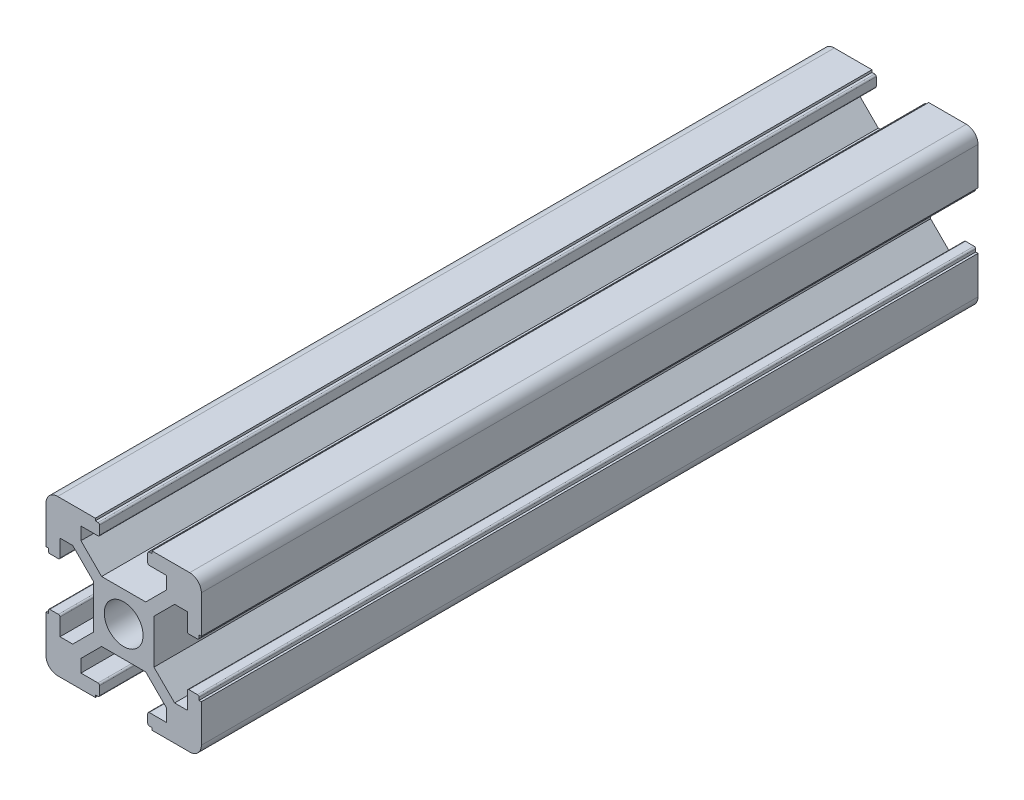
SolidWorks part; units mm, degrees
ref_plane "前视基准面" through (0, 0, 0) normal (0, 0, 1) x (1, 0, 0)
ref_plane "上视基准面" through (0, 0, 0) normal (0, 1, 0) x (1, 0, 0)
ref_plane "右视基准面" through (0, 0, 0) normal (1, 0, 0) x (0, 0, -1)
sketch "草图1" plane through (0, 0, 0) normal (0, 0, 1) x (1, 0, 0)
  line L0 (-17.5, 0) -> (33.5, 0) construction
  line L1 (0, 35.5833) -> (0, -31.0833) construction
  line L2 (3.65, 10) -> (8.5, 10)
  line L3 (10, 10) -> (10, -10) construction
  line L4 (-2.8393, 3.9) -> (2.8393, 3.9)
  line L5 (3.9, 2.8393) -> (3.9, -2.8393)
  line L6 (5.5, 8.2) -> (5.5, 6.5607)
  line L7 (3.9, 3.9) -> (10, 10) construction
  line L8 (4.4303, 3.3697) -> (6.5607, 5.5) construction
  line L9 (3.65, 10) -> (3.65, 8.2)
  line L10 (3.65, 8.2) -> (5.5, 8.2)
  line L11 (3.3697, 4.4303) -> (5.5, 6.5607) construction
  line L12 (5.5, 6.5607) -> (2.8393, 3.9)
  line L13 (6.5607, 5.5) -> (3.9, 2.8393)
  line L14 (3.3697, 4.4303) -> (9.4697, 10.5303) construction
  line L15 (4.4303, 3.3697) -> (10.5303, 9.4697) construction
  line L16 (8.2, 5.5) -> (6.5607, 5.5)
  line L17 (8.2, 3.65) -> (8.2, 5.5)
  line L18 (10, 3.65) -> (10, 8.5)
  line L19 (10, 3.65) -> (8.2, 3.65)
  line L20 (-3.3697, 4.4303) -> (-5.5, 6.5607) construction
  line L21 (-4.4303, 3.3697) -> (-6.5607, 5.5) construction
  line L22 (-3.9, 3.9) -> (-10, 10) construction
  line L23 (-10, 10) -> (-10, -10) construction
  line L24 (-10, 3.65) -> (-8.2, 3.65)
  line L25 (-10, 3.65) -> (-10, 8.5)
  line L26 (-8.2, 3.65) -> (-8.2, 5.5)
  line L27 (-8.2, 5.5) -> (-6.5607, 5.5)
  line L28 (-6.5607, 5.5) -> (-3.9, 2.8393)
  line L29 (-5.5, 6.5607) -> (-2.8393, 3.9)
  line L30 (-3.65, 8.2) -> (-5.5, 8.2)
  line L31 (-3.65, 10) -> (-3.65, 8.2)
  line L32 (-5.5, 8.2) -> (-5.5, 6.5607)
  line L33 (-3.9, 2.8393) -> (-3.9, -2.8393)
  line L34 (-3.65, 10) -> (-8.5, 10)
  line L35 (-3.9, -3.9) -> (-10, -10) construction
  line L36 (-4.4303, -3.3697) -> (-6.5607, -5.5) construction
  line L37 (-3.3697, -4.4303) -> (-5.5, -6.5607) construction
  line L38 (3.3697, -4.4303) -> (5.5, -6.5607) construction
  line L39 (4.4303, -3.3697) -> (6.5607, -5.5) construction
  line L40 (3.9, -3.9) -> (10, -10) construction
  line L41 (-3.65, -10) -> (-8.5, -10)
  line L42 (-5.5, -8.2) -> (-5.5, -6.5607)
  line L43 (-3.65, -10) -> (-3.65, -8.2)
  line L44 (-3.65, -8.2) -> (-5.5, -8.2)
  line L45 (-5.5, -6.5607) -> (-2.8393, -3.9)
  line L46 (-6.5607, -5.5) -> (-3.9, -2.8393)
  line L47 (-8.2, -5.5) -> (-6.5607, -5.5)
  line L48 (-8.2, -3.65) -> (-8.2, -5.5)
  line L49 (-10, -3.65) -> (-10, -8.5)
  line L50 (-10, -3.65) -> (-8.2, -3.65)
  line L51 (10, -3.65) -> (8.2, -3.65)
  line L52 (10, -3.65) -> (10, -8.5)
  line L53 (8.2, -3.65) -> (8.2, -5.5)
  line L54 (8.2, -5.5) -> (6.5607, -5.5)
  line L55 (6.5607, -5.5) -> (3.9, -2.8393)
  line L56 (5.5, -6.5607) -> (2.8393, -3.9)
  line L57 (3.65, -8.2) -> (5.5, -8.2)
  line L58 (3.65, -10) -> (3.65, -8.2)
  line L59 (5.5, -8.2) -> (5.5, -6.5607)
  line L60 (-2.8393, -3.9) -> (2.8393, -3.9)
  line L61 (3.65, -10) -> (8.5, -10)
  circle A0 centre (0, 0) radius 2.5
  arc A1 (-8.5, -10) -> (-10, -8.5) centre (-8.5, -8.5) cw
  arc A2 (10, -8.5) -> (8.5, -10) centre (8.5, -8.5) cw
  arc A3 (8.5, 10) -> (10, 8.5) centre (8.5, 8.5) cw
  arc A4 (-10, 8.5) -> (-8.5, 10) centre (-8.5, 8.5) cw
  point P13 (0, -3.9)
  point P42 (0, 3.9)
  point P43 (-10, 0)
  point P54 (10, 0)
  point P56 (-3.9, 0)
  point P70 (3.9, 0)
  dimension "D3" = 5
  dimension "D10" = 1.5
  dimension "D1" = 7.3
  dimension "D2" = 10
  dimension "D4" = 3.9
  dimension "D5" = 3.9
  dimension "D8" = 1.8
  dimension "D9" = 0.75
  dimension "D6" = 11
  dimension "D7" = 10
  dimension "D11" = 45
  dimension "D12" = 2.8393
extrude "凸台-拉伸2" add sketch "草图1" along normal blind 100 contours L34 A4 L25 L24 L26 L27 L28 L33 L46 L47 L48 L50 L49 A1 L41 L43 L44 L42 L45 L60 L56 L59 L57 L58 L61 A2 L52 L51 L53 L54 L55 L5 L13 L16 L17 L19 L18 A3 L2 L9 L10 L6 L12 L4 L29 L32 L30 L31
sketch "草图3" plane through (0, 0, 100) normal (0, 0, 1) x (1, 0, 0)
  line L0 (-12.6954, 0) -> (11.5012, 0) construction
  line L1 (0, 10.0863) -> (0, -11.0469) construction
  line L2 (-3.65, 8.2) -> (-3.3, 8.2)
  line L3 (3.65, 8.2) -> (3.6528, 8.2568)
  line L4 (-3.1, 8.4) -> (-3.1, 9.5)
  line L5 (3.65, 9.7) -> (3.65, 8.2)
  line L6 (-3.3, 9.7) -> (-3.65, 9.7)
  line L7 (-3.65, 8.2) -> (-3.65, 10) construction
  line L8 (-3.65, 9.7) -> (-3.65, 8.2)
  line L9 (-3.65, 8.2) -> (-3.6528, 8.2568)
  line L10 (3.3, 9.7) -> (3.65, 9.7)
  line L11 (3.1, 8.4) -> (3.1, 9.5)
  line L12 (3.65, 8.2) -> (3.3, 8.2)
  line L13 (3.65, -8.2) -> (3.3, -8.2)
  line L14 (3.1, -8.4) -> (3.1, -9.5)
  line L15 (3.3, -9.7) -> (3.65, -9.7)
  line L16 (-3.65, -8.2) -> (-3.6528, -8.2568)
  line L17 (-3.65, -9.7) -> (-3.65, -8.2)
  line L18 (-3.3, -9.7) -> (-3.65, -9.7)
  line L19 (3.65, -9.7) -> (3.65, -8.2)
  line L20 (-3.1, -8.4) -> (-3.1, -9.5)
  line L21 (3.65, -8.2) -> (3.6528, -8.2568)
  line L22 (-3.65, -8.2) -> (-3.3, -8.2)
  line L23 (0, 0) -> (9.5607, 9.5607) construction
  line L24 (-8.2, -3.65) -> (-8.2, -3.3)
  line L25 (-8.4, -3.1) -> (-9.5, -3.1)
  line L26 (-9.7, -3.3) -> (-9.7, -3.65)
  line L27 (-9.7, -3.65) -> (-8.2, -3.65)
  line L28 (-8.2, -3.65) -> (-8.2568, -3.6528)
  line L29 (8.2, 3.65) -> (8.2, 3.3)
  line L30 (8.4, 3.1) -> (9.5, 3.1)
  line L31 (9.7, 3.3) -> (9.7, 3.65)
  line L32 (9.7, 3.65) -> (8.2, 3.65)
  line L33 (8.2, 3.65) -> (8.2568, 3.6528)
  line L34 (-8.2, 3.65) -> (-8.2568, 3.6528)
  line L35 (-9.7, 3.65) -> (-8.2, 3.65)
  line L36 (-9.7, 3.3) -> (-9.7, 3.65)
  line L37 (-8.4, 3.1) -> (-9.5, 3.1)
  line L38 (-8.2, 3.65) -> (-8.2, 3.3)
  line L39 (8.2, -3.65) -> (8.2568, -3.6528)
  line L40 (9.7, -3.65) -> (8.2, -3.65)
  line L41 (9.7, -3.3) -> (9.7, -3.65)
  line L42 (8.4, -3.1) -> (9.5, -3.1)
  line L43 (8.2, -3.65) -> (8.2, -3.3)
  arc A0 (-3.1, 9.5) -> (-3.3, 9.7) centre (-3.3, 9.5) ccw
  arc A1 (-3.3, 8.2) -> (-3.1, 8.4) centre (-3.3, 8.4) ccw
  arc A2 (3.3, 8.2) -> (3.1, 8.4) centre (3.3, 8.4) cw
  arc A3 (3.1, 9.5) -> (3.3, 9.7) centre (3.3, 9.5) cw
  arc A4 (3.1, -9.5) -> (3.3, -9.7) centre (3.3, -9.5) ccw
  arc A5 (3.3, -8.2) -> (3.1, -8.4) centre (3.3, -8.4) ccw
  arc A6 (-3.3, -8.2) -> (-3.1, -8.4) centre (-3.3, -8.4) cw
  arc A7 (-3.1, -9.5) -> (-3.3, -9.7) centre (-3.3, -9.5) cw
  arc A8 (10, 8.5) -> (8.5, 10) centre (8.5, 8.5) ccw construction
  arc A9 (-9.5, -3.1) -> (-9.7, -3.3) centre (-9.5, -3.3) ccw
  arc A10 (-8.2, -3.3) -> (-8.4, -3.1) centre (-8.4, -3.3) ccw
  arc A11 (9.5, 3.1) -> (9.7, 3.3) centre (9.5, 3.3) ccw
  arc A12 (8.2, 3.3) -> (8.4, 3.1) centre (8.4, 3.3) ccw
  arc A13 (-8.2, 3.3) -> (-8.4, 3.1) centre (-8.4, 3.3) cw
  arc A14 (-9.5, 3.1) -> (-9.7, 3.3) centre (-9.5, 3.3) cw
  arc A15 (8.2, -3.3) -> (8.4, -3.1) centre (8.4, -3.3) cw
  arc A16 (9.5, -3.1) -> (9.7, -3.3) centre (9.5, -3.3) cw
  point P16 (-3.1, 9.7)
  point P19 (-3.1, 8.2)
  point P29 (3.1, 8.2)
  point P30 (3.1, 9.7)
  point P49 (3.1, -9.7)
  point P50 (3.1, -8.2)
  point P51 (-3.1, -8.2)
  point P52 (-3.1, -9.7)
  point P67 (-9.7, -3.1)
  point P68 (-8.2, -3.1)
  point P78 (9.7, 3.1)
  point P79 (8.2, 3.1)
  point P89 (-8.2, 3.1)
  point P90 (-9.7, 3.1)
  point P100 (8.2, -3.1)
  point P101 (9.7, -3.1)
  line M1 (-3.65, -10) -> (-3.65, -8.2)
  line M9 (3.65, -8.2) -> (3.65, -10)
  line M21 (8.2, 3.65) -> (10, 3.65)
  line M25 (3.65, 10) -> (3.65, 8.2)
  line M33 (-3.65, 8.2) -> (-3.65, 10)
  line M37 (-10, 3.65) -> (-8.2, 3.65)
  dimension "D3" = 0.2
  dimension "D1" = 6.2
  dimension "D2" = 1.5
extrude "凸台-拉伸3" add sketch "草图3" against normal blind 100 contours A14 L37 A13 L38 L36 M37 | L2 A1 L4 A0 L6 M33 | A3 L11 A2 L12 L10 M25 | L29 A12 L30 A11 L31 M21 | L13 A5 L14 A4 L15 M9 | A7 L20 A6 L22 L18 M1 | L43 A15 L42 A16 L41 L40 | L24 A10 L25 A9 L26 L27
